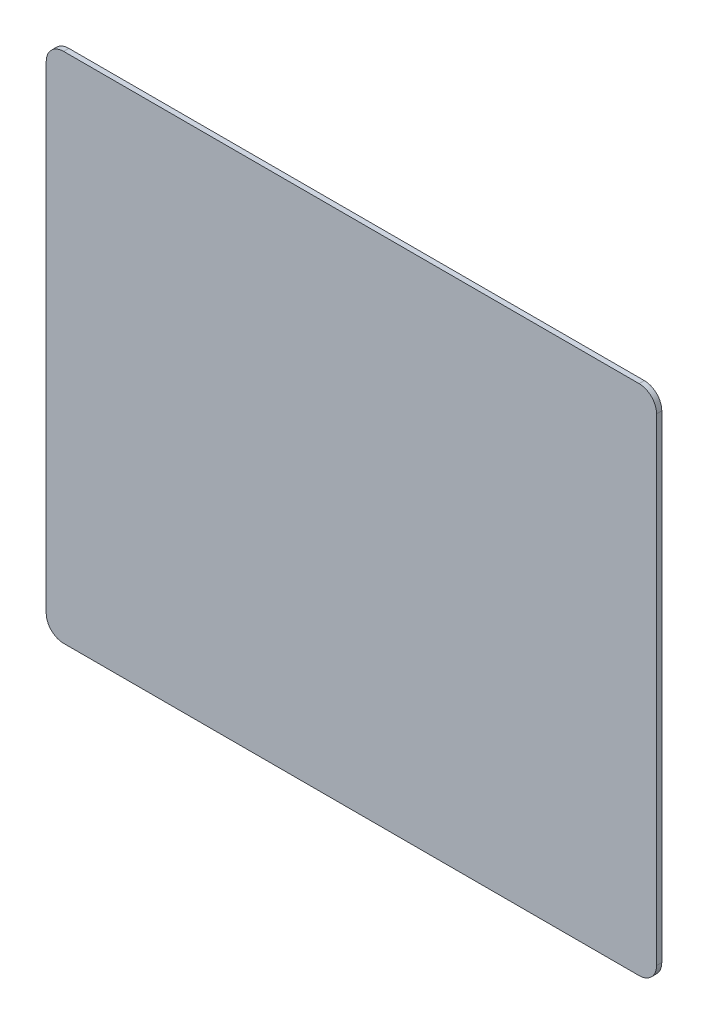
SolidWorks part; units mm, degrees
ref_plane "Front Plane" through (0, 0, 0) normal (0, 0, 1) x (1, 0, 0)
ref_plane "Top Plane" through (0, 0, 0) normal (0, 1, 0) x (1, 0, 0)
ref_plane "Right Plane" through (0, 0, 0) normal (1, 0, 0) x (0, 0, -1)
sketch "Sketch1" plane through (0, 0, 0) normal (0, 0, 1) x (1, 0, 0)
  line L1 (-350, -294) -> (350, -294)
  line L2 (-350, -294) -> (-350, 294)
  line L3 (-350, 294) -> (350, 294)
  line L4 (350, -294) -> (350, 294)
  line L5 (-350, -294) -> (350, 294) construction
  line L6 (-350, 294) -> (350, -294) construction
  point P0 (0, 0)
  dimension "D1" = 588
  dimension "D2" = 700
extrude "Boss-Extrude1" add sketch "Sketch1" along normal blind 6
fillet "Fillet1" radius 20 4 edges at (-350, 294, 3) (350, 294, 3) (350, -294, 3) (-350, -294, 3)
sketch "Sketch2" plane through (0, 0, 6) normal (0, 0, 1) x (1, 0, 0)
  line L0 (-350, 274) -> (-350, -274) construction
  line L1 (-188, -208) -> (228, -208)
  line L2 (-188, -208) -> (-188, 208)
  line L3 (-188, 208) -> (228, 208)
  line L4 (228, -208) -> (228, 208)
  line L5 (-188, -220) -> (228, -220) construction
  line L13 (-188, 104) -> (-136, 104)
  line L14 (-188, 208) -> (-136, 208)
  line L15 (-188, 208) -> (-188, 156)
  line L16 (-188, 156) -> (-136, 156)
  line L17 (-136, 208) -> (-136, 156)
  line L18 (-136, 156) -> (-136, 104)
  line L19 (-188, 52) -> (-136, 52)
  line L20 (-136, 104) -> (-136, 52)
  line L21 (-188, 0) -> (-136, 0)
  line L22 (-136, 52) -> (-136, 0)
  line L23 (-188, -52) -> (-136, -52)
  line L24 (-136, 0) -> (-136, -52)
  line L25 (-188, -104) -> (-136, -104)
  line L26 (-136, -52) -> (-136, -104)
  line L27 (-188, -156) -> (-136, -156)
  line L28 (-136, -104) -> (-136, -156)
  line L29 (-188, -208) -> (-136, -208)
  line L30 (-136, -156) -> (-136, -208)
  line L31 (-136, 156) -> (-84, 156)
  line L32 (-84, 208) -> (-84, 156)
  line L33 (-136, 104) -> (-84, 104)
  line L34 (-84, 156) -> (-84, 104)
  line L35 (-136, 52) -> (-84, 52)
  line L36 (-84, 104) -> (-84, 52)
  line L37 (-136, 0) -> (-84, 0)
  line L38 (-84, 52) -> (-84, 0)
  line L39 (-136, -52) -> (-84, -52)
  line L40 (-84, 0) -> (-84, -52)
  line L41 (-136, -104) -> (-84, -104)
  line L42 (-84, -52) -> (-84, -104)
  line L43 (-136, -156) -> (-84, -156)
  line L44 (-84, -104) -> (-84, -156)
  line L45 (-84, -156) -> (-84, -208)
  line L46 (-84, 156) -> (-32, 156)
  line L47 (-32, 208) -> (-32, 156)
  line L48 (-84, 104) -> (-32, 104)
  line L49 (-32, 156) -> (-32, 104)
  line L50 (-84, 52) -> (-32, 52)
  line L51 (-32, 104) -> (-32, 52)
  line L52 (-84, 0) -> (-32, 0)
  line L53 (-32, 52) -> (-32, 0)
  line L54 (-84, -52) -> (-32, -52)
  line L55 (-32, 0) -> (-32, -52)
  line L56 (-84, -104) -> (-32, -104)
  line L57 (-32, -52) -> (-32, -104)
  line L58 (-84, -156) -> (-32, -156)
  line L59 (-32, -104) -> (-32, -156)
  line L60 (-32, -156) -> (-32, -208)
  line L61 (-32, 156) -> (20, 156)
  line L62 (20, 208) -> (20, 156)
  line L63 (-32, 104) -> (20, 104)
  line L64 (20, 156) -> (20, 104)
  line L65 (-32, 52) -> (20, 52)
  line L66 (20, 104) -> (20, 52)
  line L67 (-32, 0) -> (20, 0)
  line L68 (20, 52) -> (20, 0)
  line L69 (-32, -52) -> (20, -52)
  line L70 (20, 0) -> (20, -52)
  line L71 (-32, -104) -> (20, -104)
  line L72 (20, -52) -> (20, -104)
  line L73 (-32, -156) -> (20, -156)
  line L74 (20, -104) -> (20, -156)
  line L75 (20, -156) -> (20, -208)
  line L76 (20, 156) -> (72, 156)
  line L77 (72, 208) -> (72, 156)
  line L78 (20, 104) -> (72, 104)
  line L79 (72, 156) -> (72, 104)
  line L80 (20, 52) -> (72, 52)
  line L81 (72, 104) -> (72, 52)
  line L82 (20, 0) -> (72, 0)
  line L83 (72, 52) -> (72, 0)
  line L84 (20, -52) -> (72, -52)
  line L85 (72, 0) -> (72, -52)
  line L86 (20, -104) -> (72, -104)
  line L87 (72, -52) -> (72, -104)
  line L88 (20, -156) -> (72, -156)
  line L89 (72, -104) -> (72, -156)
  line L90 (72, -156) -> (72, -208)
  line L91 (72, 156) -> (124, 156)
  line L92 (124, 208) -> (124, 156)
  line L93 (72, 104) -> (124, 104)
  line L94 (124, 156) -> (124, 104)
  line L95 (72, 52) -> (124, 52)
  line L96 (124, 104) -> (124, 52)
  line L97 (72, 0) -> (124, 0)
  line L98 (124, 52) -> (124, 0)
  line L99 (72, -52) -> (124, -52)
  line L100 (124, 0) -> (124, -52)
  line L101 (72, -104) -> (124, -104)
  line L102 (124, -52) -> (124, -104)
  line L103 (72, -156) -> (124, -156)
  line L104 (124, -104) -> (124, -156)
  line L105 (124, -156) -> (124, -208)
  line L106 (124, 156) -> (176, 156)
  line L107 (176, 208) -> (176, 156)
  line L108 (124, 104) -> (176, 104)
  line L109 (176, 156) -> (176, 104)
  line L110 (124, 52) -> (176, 52)
  line L111 (176, 104) -> (176, 52)
  line L112 (124, 0) -> (176, 0)
  line L113 (176, 52) -> (176, 0)
  line L114 (124, -52) -> (176, -52)
  line L115 (176, 0) -> (176, -52)
  line L116 (124, -104) -> (176, -104)
  line L117 (176, -52) -> (176, -104)
  line L118 (124, -156) -> (176, -156)
  line L119 (176, -104) -> (176, -156)
  line L120 (176, -156) -> (176, -208)
  line L121 (176, 156) -> (228, 156)
  line L122 (228, 208) -> (228, 156)
  line L123 (176, 104) -> (228, 104)
  line L124 (228, 156) -> (228, 104)
  line L125 (176, 52) -> (228, 52)
  line L126 (228, 104) -> (228, 52)
  line L127 (176, 0) -> (228, 0)
  line L128 (228, 52) -> (228, 0)
  line L129 (176, -52) -> (228, -52)
  line L130 (228, 0) -> (228, -52)
  line L131 (176, -104) -> (228, -104)
  line L132 (228, -52) -> (228, -104)
  line L133 (176, -156) -> (228, -156)
  line L134 (228, -104) -> (228, -156)
  line L135 (228, -156) -> (228, -208)
  line L137 (-193, -208) -> (-193, 208) construction
  line L138 (330, 294) -> (-330, 294) construction
  line L139 (-330, -294) -> (330, -294) construction
  line L144 (-315, -279) -> (-243.7, -279)
  line L151 (-315, -279) -> (-315, -254.6)
  line L152 (-315, -254.6) -> (-243.7, -254.6)
  line L153 (-243.7, -279) -> (-243.7, -254.6)
  line L154 (-262, -225) -> (302, -225)
  line L155 (-272, -215) -> (-272, 215)
  line L156 (-262, 225) -> (302, 225)
  line L157 (312, -215) -> (312, 215)
  line L158 (-272, -225) -> (312, 225) construction
  line L159 (-272, 225) -> (312, -225) construction
  line L163 (188.4646, -283.6) -> (311, -283.6)
  line L168 (-320.35, -283.6) -> (-238.35, -283.6)
  line L169 (-320.35, -283.6) -> (-320.35, -249.6)
  line L170 (-320.35, -249.6) -> (-238.35, -249.6)
  line L171 (-238.35, -283.6) -> (-238.35, -249.6)
  line L172 (-320.35, -283.6) -> (-238.35, -249.6) construction
  line L173 (-320.35, -249.6) -> (-238.35, -283.6) construction
  circle A41 centre (-252, -155.5) radius 13
  circle A42 centre (-220, -178) radius 15
  circle A43 centre (-220, -133) radius 15
  circle A44 centre (-220, -88) radius 15
  circle A45 centre (-220, -43) radius 15
  circle A46 centre (-220, 2) radius 15
  circle A47 centre (-220, 47) radius 15
  circle A48 centre (-220, 92) radius 15
  circle A49 centre (-220, 137) radius 15
  circle A50 centre (-220, 182) radius 15
  circle A51 centre (-252, -110.5) radius 13
  circle A52 centre (-252, -65.5) radius 13
  circle A53 centre (-252, -20.5) radius 13
  circle A54 centre (-252, 24.5) radius 13
  circle A55 centre (-252, 69.5) radius 13
  circle A56 centre (-252, 114.5) radius 13
  circle A57 centre (-252, 159.5) radius 13
  circle A58 centre (260, -178) radius 15
  circle A59 centre (292, 159.5) radius 13
  circle A60 centre (292, 114.5) radius 13
  circle A61 centre (292, 69.5) radius 13
  circle A62 centre (292, 24.5) radius 13
  circle A63 centre (292, -20.5) radius 13
  circle A64 centre (292, -65.5) radius 13
  circle A65 centre (292, -110.5) radius 13
  circle A66 centre (260, 182) radius 15
  circle A67 centre (260, 137) radius 15
  circle A68 centre (260, 92) radius 15
  circle A69 centre (260, 47) radius 15
  circle A70 centre (260, 2) radius 15
  circle A71 centre (260, -43) radius 15
  circle A72 centre (260, -88) radius 15
  circle A73 centre (260, -133) radius 15
  circle A74 centre (292, -155.5) radius 13
  arc A75 (302, 225) -> (312, 215) centre (302, 215) cw
  arc A76 (-272, 215) -> (-262, 225) centre (-262, 215) cw
  arc A77 (302, -225) -> (312, -215) centre (302, -215) ccw
  arc A78 (-262, -225) -> (-272, -215) centre (-262, -215) cw
  circle A79 centre (-315, -225) radius 14.4
  text T0 "A B C D E F G H" font "Calibri" height in points 26
  text T1 "1 2 3 4 5 6 7 8" font "Calibri" height in points 26
  text T2 "Masteroppgave Emil Aasen Skogheim" font "Century Gothic" height in points 16
  point P224 (210.3589, -283.0084)
  point P225 (189.4646, -283.0084)
  point P226 (-279.35, -266.6)
  dimension "D4" = 30
  dimension "D8" = 45
  dimension "D16" = 32
  dimension "D17" = 450
  dimension "D21" = 416
  dimension "D26" = 71.3
  dimension "D29" = 10
  dimension "D6" = 26
  dimension "D27" = 15
  dimension "D28" = 12
  dimension "D31" = 35.65
  dimension "D30" = 28.8
  dimension "D1" = 416
  dimension "D2" = 162
  dimension "D3" = 208
  dimension "D5" = 22.5
  dimension "D7" = 30
  dimension "D9" = 52
  dimension "D10" = 8
  dimension "D12" = 45
  dimension "D13" = 8
  dimension "D15" = 32
  dimension "D18" = 584
  dimension "D20" = 24.4
  dimension "D22" = 12
  dimension "D23" = 416
  dimension "D24" = 0
  dimension "D25" = 5
  dimension "D14" = 9
  dimension "D32" = 35
  dimension "D33" = 82
  dimension "D34" = 34
  dimension "D11" = 8
